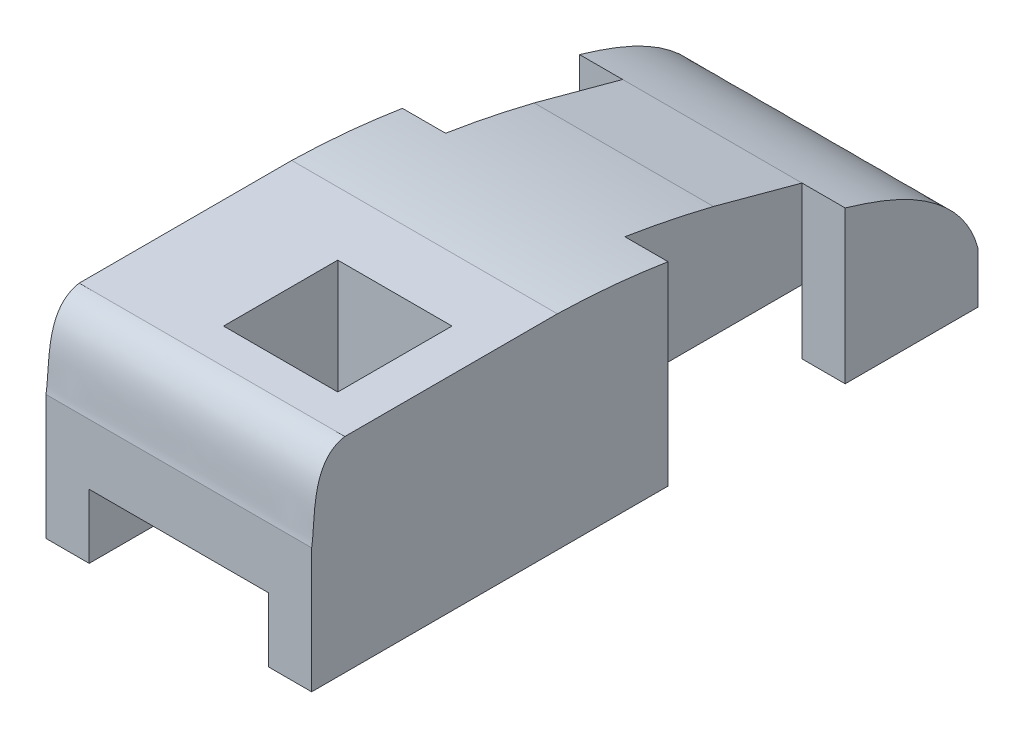
SolidWorks part; units mm, degrees
ref_plane "前视基准面" through (0, 0, 0) normal (0, 0, 1) x (1, 0, 0)
ref_plane "上视基准面" through (0, 0, 0) normal (0, 1, 0) x (1, 0, 0)
ref_plane "右视基准面" through (0, 0, 0) normal (1, 0, 0) x (0, 0, -1)
other "Configuration Table"
sketch "草图1" plane through (0, 0, 0) normal (0, 1, 0) x (1, 0, 0)
  line L1 (-50, 92.5) -> (50, 92.5)
  line L2 (-50, 92.5) -> (-50, -92.5)
  line L3 (-50, -92.5) -> (50, -92.5)
  line L4 (50, 92.5) -> (50, -92.5)
  line L5 (-50, 92.5) -> (50, -92.5) construction
  line L6 (-50, -92.5) -> (50, 92.5) construction
  point P0 (0, 0)
  dimension "D1" = 100
  dimension "D2" = 185
extrude "凸台-拉伸1" add sketch "草图1" along normal blind 100
sketch "草图2" plane through (0, 0, 92.5) normal (0, 0, 1) x (1, 0, 0)
  line L0 (-20.8417, 0) -> (-20.8417, 3.8) construction
  line L1 (-50, 0) -> (50, 0) construction
  line L2 (-20.8417, 3.8) -> (75.1632, 3.8) construction
  line L3 (75.1632, 3.8) -> (-71.0613, 3.8) construction
  line L4 (-50, 5.664) -> (-50, -9.7456) construction
  line L5 (-50, 100) -> (-50, 0) construction
  line L7 (50, 0) -> (-50, 0)
  line L8 (50, 0) -> (50, 3.8)
  line L9 (50, 3.8) -> (-50, 3.8)
  line L10 (-50, 0) -> (-50, 3.8)
  dimension "D1" = 3.8
extrude "切除-拉伸1" cut sketch "草图2" against normal offset from surface (155 mm away) 30 up to face at (0, 50, -92.5)
sketch "草图3" plane through (0, 0, 92.5) normal (0, 0, 1) x (1, 0, 0)
  line L0 (-20, 101.4471) -> (-20, -5.8655) construction
  line L1 (-4.3, 4.1859) -> (4.3, 4.1859) construction
  line L2 (-50, 3.8) -> (-20, 3.8) construction
  line L3 (-50, 3.8) -> (50, 3.8) construction
  line L4 (50, 3.8) -> (20, 3.8) construction
  line L5 (50, 3.8) -> (-50, 3.8) construction
  line L6 (20, 3.8) -> (20, 102.7774) construction
  line L7 (0, 0) -> (0, 12.6714) construction
  line L8 (-3.51, 3.8) -> (3.51, 3.8)
  line L9 (0, 3.8) -> (7.456, 3.8) construction
  line L10 (-9.3719, 10.6927) -> (9.3719, 10.6927) construction
  line L11 (-4.5, 11.5021) -> (4.5, 11.5021) construction
  line L12 (-9.3719, 10.6927) -> (-9.3719, 3.8) construction
  line L13 (-9.3719, 10.6927) -> (-4.3, 4.1859)
  line L14 (-4.3, 4.1859) -> (-4.3, 3.8) construction
  line L15 (8.9765, 11.5021) -> (8.9765, 10.6927) construction
  line L16 (9.3719, 10.6927) -> (4.3, 4.1859)
  line L17 (-4.5, 11.5021) -> (-8.9765, 11.5021)
  line L18 (4.5, 11.5021) -> (8.9765, 11.5021)
  line L19 (-8.9765, 11.5021) -> (-8.9765, 10.6927) construction
  line L21 (-4.5, 16.0021) -> (4.5, 16.0021) construction
  line L24 (-50, 100) -> (-50, 3.8) construction
  line L25 (-50, 16.0021) -> (-50, 3.8)
  line L26 (-50, 3.8) -> (-3.51, 3.8)
  line L28 (50, 100) -> (50, 3.8) construction
  line L29 (50, 16.0021) -> (50, 3.8)
  line L30 (50, 3.8) -> (3.51, 3.8)
  line L33 (20.5, 3.8) -> (3.51, 3.8)
  line L36 (-20.5, 3.8) -> (-3.51, 3.8)
  line L37 (0, 16.0021) -> (4, 16.0021)
  line L38 (0, 16.0021) -> (-4, 16.0021)
  line L39 (4, 16.0021) -> (4, 12.0021)
  line L40 (-4, 16.0021) -> (-4, 12.0021)
  line L41 (-4, 16.0021) -> (-20, 16.0021)
  line L42 (-20, 16.0021) -> (-20, 3.8)
  line L43 (-20, 3.8) -> (-3.51, 3.8)
  line L44 (4, 16.0021) -> (20, 16.0021)
  line L45 (20, 16.0021) -> (20, 3.8)
  line L46 (20, 3.8) -> (3.51, 3.8)
  arc A0 (-4.3, 4.1859) -> (-3.51, 3.8) centre (-3.51, 4.8016) ccw
  arc A1 (3.51, 3.8) -> (4.3, 4.1859) centre (3.51, 4.8016) ccw
  arc A2 (-9.3719, 10.6927) -> (-8.9765, 11.5021) centre (-8.3456, 10.6927) cw
  arc A3 (8.9765, 11.5021) -> (9.3719, 10.6927) centre (8.9765, 11.0008) cw
  arc A4 (-4, 12.0021) -> (-4.5, 11.5021) centre (-4.5, 12.0021) cw
  arc A5 (4, 12.0021) -> (4.5, 11.5021) centre (4.5, 12.0021) ccw
  point P21 (0, 3.8)
  point P24 (0, 10.6927)
  point P28 (0, 11.5021)
  point P29 (0, 4.1859)
  line M35 (-50, 3.8) -> (50, 3.8)
  dimension "D10" = 4.5
  dimension "D1" = 30
  dimension "D2" = 30
  dimension "D3" = 7.02
  dimension "D4" = 6.8927
  dimension "D5" = 8.25
  dimension "D6" = 8.6
  dimension "D7" = 4.4765
  dimension "D8" = 9
  dimension "D9" = 4.4765
  dimension "D11" = 4
  dimension "D12" = 4
  dimension "D13" = 4
extrude "切除-拉伸2" cut sketch "草图3" against normal offset from surface (155 mm away) 30 contours A4 L40 L41 L42 L36 A0 L13 A2 L17 | L39 A5 L18 A3 L16 A1 L45 L44 M35 up to face at (0, 50, -92.5)
sketch "草图4" plane through (0, 100, 0) normal (0, 1, 0) x (1, 0, 0)
  line L0 (50, -77.1603) -> (20.5, -77.1603) construction
  line L1 (50, -92.5) -> (50, 92.5) construction
  line L2 (20.5, -77.1603) -> (20.5, -102.6857) construction
  line L3 (20.5, -102.6857) -> (20.5, 96.3461) construction
  line L4 (57.5619, -92.5) -> (57.5619, -63) construction
  line L5 (-50, -92.5) -> (50, -92.5) construction
  line L6 (-68.401, -63) -> (56.5569, -63) construction
  line L8 (20.5, -63) -> (-5, -63)
  line L9 (20.5, -63) -> (20.5, -37.5)
  line L10 (20.5, -37.5) -> (-5, -37.5)
  line L11 (-5, -63) -> (-5, -37.5)
  dimension "D1" = 29.5
  dimension "D2" = 29.5
  dimension "D3" = 25.5
  dimension "D4" = 25.5
extrude "切除-拉伸3" cut sketch "草图4" against normal blind 79
sketch "草图6" plane through (0, 100, 0) normal (0, 1, 0) x (1, 0, 0)
  line L0 (-39.7063, 92.5) -> (-39.7063, 82.5)
  line L1 (50, 92.5) -> (-50, 92.5) construction
  line L2 (-39.7063, 82.5) -> (82.0818, 82.5)
  line L3 (-39.7063, 82.5) -> (-63.7302, 82.5)
  line M6 (50, -92.5) -> (50, 92.5)
  line M7 (50, 92.5) -> (-50, 92.5)
  line M8 (-50, 92.5) -> (-50, -92.5)
  dimension "D1" = 10
extrude "切除-拉伸4" cut sketch "草图6" against normal through all contours L0 L2 M6 M7 | L3 L0 M7 M8
sketch "草图7" plane through (-50, 0, 0) normal (-1, 0, 0) x (0, 0, 1)
  line L0 (-62.5, 3.8) -> (-82.5, 3.8)
  line L1 (-82.5, 0) -> (-82.5, 100) construction
  line M3 (-82.5, 100) -> (-82.5, 0)
  line M4 (-82.5, 0) -> (-62.5, 0)
  line M5 (-62.5, 0) -> (-62.5, 3.8)
extrude "切除-拉伸5" cut sketch "草图7" against normal through all and the other way through all contours L0 M5 M3 M4
sketch "草图9" plane through (0, 0, 92.5) normal (0, 0, 1) x (1, 0, 0)
  line L0 (-9.3719, 10.6927) -> (-9.3719, 13.2927)
  line L1 (-9.3719, 13.2927) -> (-4, 13.2927)
  line L2 (-4, 12.0021) -> (-4, 16.0021) construction
  line L3 (-9.3719, 10.6927) -> (9.3719, 10.6927)
  line L4 (9.3719, 10.6927) -> (9.3719, 13.2927)
  line L5 (9.3719, 13.2927) -> (4, 13.2927)
  line L6 (4, 16.0021) -> (4, 12.0021) construction
  line L7 (-4, 13.2927) -> (4, 13.2927)
  dimension "D1" = 2.6
extrude "凸台-拉伸4" add sketch "草图9" against normal blind 160
sketch "草图10" plane through (0, 0, 92.5) normal (0, 0, 1) x (1, 0, 0)
  line L0 (-20, 16.0021) -> (-20, 17.8021)
  line L1 (-20, 17.8021) -> (-4, 17.8021)
  line L2 (-4, 17.8021) -> (-4, 16.0021)
  line L4 (4, 16.0021) -> (4, 17.8021)
  line L5 (4, 17.8021) -> (19.9985, 17.8021)
  line L6 (19.9985, 17.8021) -> (20, 16.0021)
  line L7 (20, 16.0021) -> (4, 16.0021) construction
  line L8 (4, 16.0021) -> (20, 16.0021) construction
  line L9 (-20, 16.0021) -> (-4, 16.0021)
  line L10 (4, 16.0021) -> (20, 16.0021)
  dimension "D1" = 1.8
  dimension "D2" = 1.8
extrude "切除-拉伸6" cut sketch "草图10" against normal blind 155
sketch "草图13" plane through (0, 3.8, 0) normal (0, -1, 0) x (1, 0, 0)
  line L11 (-30, 92.5) -> (-30, -82.5)
  line L12 (50, -82.5) -> (-50, -82.5) construction
  line L13 (-30, -82.5) -> (-50, -82.5)
  line L14 (-50, 92.5) -> (-30, 92.5)
  line L16 (-50, 92.5) -> (-50, -82.5)
  line L17 (50, 92.5) -> (30, 92.5)
  line L18 (50, 92.5) -> (20, 92.5) construction
  line L19 (30, 92.5) -> (30, -82.5)
  line L20 (30, -82.5) -> (50, -82.5)
  line L21 (50, -82.5) -> (50, 92.5)
  dimension "D3" = 20
  dimension "D4" = 20
extrude "切除-拉伸7" cut sketch "草图13" against normal through all
sketch "草图14" plane through (30, 0, 0) normal (1, 0, 0) x (0, 0, -1)
  line L0 (-92.5, 100) -> (-92.5, 50)
  line L1 (-92.5, 100) -> (-92.5, 3.8) construction
  line L2 (-92.5, 50) -> (82.5, 50)
  line L3 (82.5, 100) -> (82.5, 3.8) construction
  line L4 (82.5, 50) -> (82.5, 100)
  line L5 (82.5, 100) -> (-92.5, 100)
  dimension "D1" = 50
extrude "切除-拉伸8" cut sketch "草图14" against normal through all
sketch "草图15" plane through (0, 3.8, 0) normal (0, -1, 0) x (1, 0, 0)
  line L0 (-30, -82.5) -> (-30, -72.5)
  line L1 (-30, -82.5) -> (-30, 92.5) construction
  line L2 (-30, -72.5) -> (30, -72.5)
  line L3 (30, 92.5) -> (30, -82.5) construction
  line L4 (30, -72.5) -> (30, -82.5)
  line L5 (30, -82.5) -> (-30, -82.5)
  dimension "D1" = 10
extrude "切除-拉伸9" cut sketch "草图15" against normal through all
sketch "草图16" plane through (0, 50, 0) normal (0, 1, 0) x (1, 0, 0)
  line L0 (30, -92.5) -> (30, 72.5) construction
  line L1 (-30, -92.5) -> (30, -92.5)
  line L2 (-30, -92.5) -> (-30, -78)
  line L3 (-30, -78) -> (30, -78)
  line L4 (30, -92.5) -> (30, -78)
  dimension "D1" = 14.5
extrude "切除-拉伸10" cut sketch "草图16" against normal through all
sketch "草图17" plane through (30, 0, 0) normal (1, 0, 0) x (0, 0, -1)
  line L0 (-78, 3.8) -> (72.5, 3.8) construction
  line L1 (-78, 50) -> (-63, 50) construction
  line L2 (-78, 50) -> (-78, 3.8) construction
  line L3 (-78, 3.8) -> (-63, 3.8) construction
  line L4 (-63, 50) -> (-63, 3.8) construction
  line L5 (72.5, 50) -> (72.5, 3.8) construction
  line L6 (-63, 50) -> (-37.5, 50)
  line L7 (-63, 50) -> (-63, 3.8)
  line L8 (-63, 3.8) -> (-37.5, 3.8)
  line L9 (-37.5, 50) -> (-37.5, 3.8)
  line L10 (-37.5, 50) -> (-22.5, 50)
  line L11 (-37.5, 50) -> (-37.5, 3.8)
  line L12 (-37.5, 3.8) -> (-22.5, 3.8)
  line L13 (-22.5, 50) -> (-22.5, 3.8)
  line L14 (72.5, 15.3113) -> (72.5, 3.8)
  line L15 (72.5, 3.8) -> (-22.5, 3.8)
  line L16 (-22.5, 50) -> (72.5, 50)
  line L17 (72.5, 50) -> (72.5, 15.3113)
  spline S0 degree 3 poles (-22.5, 50) (-9.3307, 49.7061) (11.0858, 46.8271) (38.2398, 39.499) (59.6886, 33.2729) (70.6797, 22.2955) (72.5, 15.3113) knots 0 0 0 0 0.374533 0.581855 0.802431 1 1 1 1
  line M3 (72.5, 50) -> (-78, 50)
  line M6 (72.5, 3.8) -> (72.5, 50)
  dimension "D1" = 15
  dimension "D2" = 25.5
  dimension "D3" = 15
extrude "切除-拉伸11" cut sketch "草图17" against normal through all contours S0 M3 M6
sketch "草图24" plane through (0, 0, 78) normal (0, 0, 1) x (1, 0, 0)
  line L0 (9.3719, 11.309) -> (9.3719, 10.6927)
  line L1 (9.3719, 10.6927) -> (4.3, 4.1859) construction
  arc A0 (9.3719, 10.6927) -> (9.3719, 11.309) centre (8.9765, 11.0008) ccw construction
  arc M6 (9.3719, 10.6927) -> (9.3719, 11.309) centre (8.9765, 11.0008) ccw
extrude "切除-拉伸21" cut sketch "草图24" against normal blind 140.5 and the other way through all contours L0 M6
sketch "草图28" plane through (30, 0, 0) normal (1, 0, 0) x (0, 0, -1)
  line L0 (-78, 3.8) -> (72.5, 3.8) construction
  line L1 (-78, 50) -> (-63, 50)
  line L2 (-78, 50) -> (-78, 3.8)
  line L3 (-78, 3.8) -> (-63, 3.8)
  line L4 (-63, 50) -> (-63, 3.8)
  spline S0 degree 3 poles (-70.5, 50) (-78.4109, 48.6564) (-77.0738, 36.8433) (-78, 31.9829) knots 0 0 0 0 1 1 1 1
  line M9 (-78, 50) -> (-78, 3.8)
  dimension "D1" = 15
extrude "切除-拉伸26" cut sketch "草图28" against normal through all contours S0 L1 M9
sketch "草图34" plane through (0, 3.8, 0) normal (0, -1, 0) x (1, 0, 0)
  line L0 (-30, -72.5) -> (-30, 78) construction
  line L1 (-20, -62.5) -> (-30, -62.5)
  line L2 (-20, -62.5) -> (-20, -42.5)
  line L3 (-20, -42.5) -> (-30, -42.5)
  line L4 (-30, -62.5) -> (-30, -42.5)
  line L5 (30, 78) -> (30, -72.5) construction
  line L6 (20, -62.5) -> (30, -62.5)
  line L7 (20, -62.5) -> (20, -42.5)
  line L8 (20, -42.5) -> (30, -42.5)
  line L9 (30, -62.5) -> (30, -42.5)
  line L10 (-9.3719, -62.5) -> (-9.3719, 78) construction
  line L11 (-9.3719, -42.5) -> (9.3719, -42.5)
  line L12 (-9.3719, -42.5) -> (-9.3719, -62.5)
  line L13 (-9.3719, -62.5) -> (9.3719, -62.5)
  line L14 (9.3719, -42.5) -> (9.3719, -62.5)
  line L15 (20, -62.5) -> (3.51, -62.5) construction
  line L16 (4.3, -62.5) -> (9.3719, -62.5) construction
  line L17 (20, -62.5) -> (20, 78) construction
  line L18 (-20, -42.5) -> (-30, -42.5)
  line L19 (-20, -42.5) -> (-20, -22.5)
  line L20 (-20, -22.5) -> (-30, -22.5)
  line L21 (-30, -42.5) -> (-30, -22.5)
  line L22 (-9.3719, -22.5) -> (9.3719, -22.5)
  line L23 (-9.3719, -22.5) -> (-9.3719, -42.5)
  line L24 (-9.3719, -42.5) -> (9.3719, -42.5)
  line L25 (9.3719, -22.5) -> (9.3719, -42.5)
  line L26 (20, -22.5) -> (30, -22.5)
  line L27 (20, -22.5) -> (20, -42.5)
  line L28 (20, -42.5) -> (30, -42.5)
  line L29 (30, -22.5) -> (30, -42.5)
  line L31 (-20, -22.5) -> (-30, -22.5)
  line L32 (-20, -22.5) -> (-20, -2.5)
  line L33 (-20, -2.5) -> (-30, -2.5)
  line L34 (-30, -22.5) -> (-30, -2.5)
  line L35 (-20, -2.5) -> (-30, -2.5)
  line L36 (-20, -2.5) -> (-20, 78)
  line L37 (-20, 78) -> (-30, 78)
  line L38 (-30, -2.5) -> (-30, 78)
  line L39 (-9.3719, 78) -> (9.3719, 78)
  line L40 (-9.3719, 78) -> (-9.3719, -2.5)
  line L41 (-9.3719, -2.5) -> (9.3719, -2.5)
  line L42 (9.3719, 78) -> (9.3719, -2.5)
  line L43 (20, 78) -> (30, 78)
  line L44 (20, 78) -> (20, -2.5)
  line L45 (20, -2.5) -> (30, -2.5)
  line L46 (30, 78) -> (30, -2.5)
  line M6 (30, -72.5) -> (30, 78)
  line M8 (20, 78) -> (20, -62.5)
  line M14 (-20, -62.5) -> (-20, 78)
  line M16 (-30, 78) -> (-30, -72.5)
  dimension "D1" = 20
  dimension "D2" = 20
  dimension "D3" = 20
  dimension "D4" = 20
  dimension "D5" = 20
extrude "切除-拉伸31" cut sketch "草图34" against normal through all contours L20 L3 M14 M16 | L26 L8 M8 M6
sketch "草图35" plane through (0, 3.8, 0) normal (0, -1, 0) x (1, 0, 0)
  line L0 (-30, -22.5) -> (-30, 78) construction
  line L1 (-20, -22.5) -> (-30, -22.5)
  line L2 (-20, -22.5) -> (-20, -2.5)
  line L3 (-20, -2.5) -> (-30, -2.5)
  line L4 (-30, -22.5) -> (-30, -2.5)
  line L5 (-9.3719, -62.5) -> (-9.3719, 78) construction
  line L6 (-9.3719, -2.5) -> (9.3719, -2.5)
  line L7 (-9.3719, -2.5) -> (-9.3719, -22.5)
  line L8 (-9.3719, -22.5) -> (9.3719, -22.5)
  line L9 (9.3719, -2.5) -> (9.3719, -22.5)
  line L10 (20, -22.5) -> (20, 78) construction
  line L11 (20, -2.5) -> (30, -2.5)
  line L12 (20, -2.5) -> (20, -22.5)
  line L13 (20, -22.5) -> (30, -22.5)
  line L14 (30, -2.5) -> (30, -22.5)
  line L15 (30, 78) -> (30, -22.5) construction
  line L17 (-9.3719, 78) -> (9.3719, 78)
  line L18 (-9.3719, 78) -> (-9.3719, -2.5)
  line L19 (-9.3719, -2.5) -> (9.3719, -2.5)
  line L20 (9.3719, 78) -> (9.3719, -2.5)
  dimension "D1" = 20
extrude "切除-拉伸32" cut sketch "草图35" against normal blind 14 contours L20 L17 L18 L6
sketch "草图40" plane through (0, 0, -2.5) normal (0, 0, 1) x (1, 0, 0)
  line L0 (9.3719, 13.2927) -> (4, 13.2927) construction
  line L1 (4, 17.8021) -> (3.75, 17.8021)
  line L2 (4, 17.8021) -> (4, 13.2927)
  line L3 (4, 13.2927) -> (3.75, 13.2927)
  line L4 (3.75, 17.8021) -> (3.75, 13.2927)
  line L5 (-4, 17.8) -> (4, 17.8) construction
  line L6 (-4, 13.2927) -> (-3.75, 13.2927)
  line L7 (-4, 13.2927) -> (-4, 17.8)
  line L8 (-4, 17.8) -> (-3.75, 17.8)
  line L9 (-3.75, 13.2927) -> (-3.75, 17.8)
  line L10 (9.3719, 10.6927) -> (9.3719, 13.2927) construction
  line L11 (-9.3719, 13.2927) -> (9.3719, 13.2927)
  line L12 (-9.3719, 13.2927) -> (-9.3719, 12.7927)
  line L13 (-9.3719, 12.7927) -> (9.3719, 12.7927)
  line L14 (9.3719, 13.2927) -> (9.3719, 12.7927)
  line L16 (-3.75, 13.2927) -> (3.75, 13.2927)
  line L17 (-3.75, 13.2927) -> (-3.75, 12.7927)
  line L18 (-3.75, 12.7927) -> (3.75, 12.7927)
  line L19 (3.75, 13.2927) -> (3.75, 12.7927)
  line M7 (9.3719, 10.6927) -> (9.3719, 13.2927)
  line M8 (9.3719, 13.2927) -> (4, 13.2927)
  line M9 (4, 13.2927) -> (4, 17.8)
  line M10 (4, 17.8) -> (-4, 17.8)
  line M12 (-4, 13.2927) -> (-9.3719, 13.2927)
  line M13 (-9.3719, 13.2927) -> (-9.3719, 10.6927)
  dimension "D1" = 0.25
  dimension "D2" = 0.25
  dimension "D3" = 0.5
extrude "切除-拉伸35" cut sketch "草图40" against normal blind 60 contours L4 L3 M10 M9 | L3 L19 L13 M7 M8 | L17 L6 L13 M12 M13
sketch "草图41" plane through (0, 0, 78) normal (0, 0, 1) x (1, 0, 0)
  line L0 (-20, 3.8) -> (-30, 3.8) construction
  line L1 (-20, 17.8021) -> (19.9985, 17.8021)
  line L3 (-20, 18.3021) -> (19.9985, 18.3021)
  line L5 (-3.75, 17.8) -> (3.75, 17.8)
  line L6 (-3.75, 17.8) -> (-3.75, 18.3021)
  line L8 (3.75, 17.8) -> (3.75, 18.3021)
  line L11 (-20, 17.8) -> (-3.75, 17.8)
  line L17 (-20, 18.3021) -> (-20.25, 18.3021)
  line L18 (-20, 18.3021) -> (-20, 3.8)
  line L19 (-20, 3.8) -> (-20.25, 3.8)
  line L20 (-20.25, 18.3021) -> (-20.25, 3.8)
  line L21 (30, 3.8) -> (20, 3.8) construction
  line L22 (19.9985, 18.3021) -> (20.2485, 18.3021)
  line L23 (19.9985, 18.3021) -> (19.9985, 3.8)
  line L24 (19.9985, 3.8) -> (20.2485, 3.8)
  line L25 (20.2485, 18.3021) -> (20.2485, 3.8)
  dimension "D1" = 0.5
  dimension "D2" = 0.25
  dimension "D3" = 0.25
extrude "切除-拉伸36" cut sketch "草图41" against normal blind 140.5
sketch "草图43" plane through (0, 0, 78) normal (0, 0, 1) x (1, 0, 0)
  line L0 (-4, 17.8) -> (4, 17.8) construction
  line L1 (-4, 17.8021) -> (-3.75, 17.8021)
  line L2 (-4, 17.8021) -> (-4, 17.8)
  line L3 (-4, 17.8) -> (-3.75, 17.8)
  line L4 (-3.75, 17.8021) -> (-3.75, 17.8)
  line L5 (-4, 17.8) -> (-3.75, 17.8) construction
  line L7 (3.75, 17.8021) -> (4, 17.8021)
  line L8 (3.75, 17.8021) -> (3.75, 17.8)
  line L9 (3.75, 17.8) -> (4, 17.8)
  line L10 (4, 17.8021) -> (4, 17.8)
extrude "切除-拉伸37" cut sketch "草图43" against normal blind 140.5
sketch "草图44" plane through (0, 0, 78) normal (0, 0, 1) x (1, 0, 0)
  line L1 (-3.75, 18.3021) -> (3.75, 18.3021)
  line L2 (-3.75, 18.3021) -> (-3.75, 17.8)
  line L3 (-3.75, 17.8) -> (3.75, 17.8)
  line L4 (3.75, 18.3021) -> (3.75, 17.8)
extrude "切除-拉伸38" cut sketch "草图44" against normal offset from surface (80.4999 mm away) 0.0001 up to face at (0, 10.3288, -2.5)
sketch "草图45" plane through (0, 3.8, 0) normal (0, -1, 0) x (1, 0, 0)
  line L0 (-30, -22.5) -> (-30, 78) construction
  line L1 (-30, -2.5) -> (-20.25, -2.5)
  line L2 (-30, -2.5) -> (-30, -22.5)
  line L3 (-30, -22.5) -> (-20.25, -22.5)
  line L4 (-20.25, -2.5) -> (-20.25, -22.5)
  line L5 (-9.3719, -2.5) -> (-4.3, -2.5) construction
  line L6 (20.2485, -22.5) -> (20.2485, 78) construction
  line L7 (20.2485, -2.5) -> (30, -2.5)
  line L8 (20.2485, -2.5) -> (20.2485, -22.5)
  line L9 (20.2485, -22.5) -> (30, -22.5)
  line L10 (30, -2.5) -> (30, -22.5)
extrude "切除-拉伸39" cut sketch "草图45" against normal through all
sketch "草图46" plane through (0, 18.3021, 0) normal (0, -1, 0) x (1, 0, 0)
  line L1 (20, -22.5) -> (20.2485, -22.5)
  line L2 (20, -22.5) -> (20, -42.5)
  line L3 (20, -42.5) -> (20.2485, -42.5)
  line L4 (20.2485, -22.5) -> (20.2485, -42.5)
  line L5 (-20, -22.5) -> (-20.25, -22.5)
  line L6 (-20, -22.5) -> (-20, -42.5)
  line L7 (-20, -42.5) -> (-20.25, -42.5)
  line L8 (-20.25, -22.5) -> (-20.25, -42.5)
extrude "凸台-拉伸5" add sketch "草图46" against normal through all
sketch "草图47" plane through (-20.25, 0, 0) normal (-1, 0, 0) x (0, 0, 1)
  spline S0 degree 1 poles (-42.5, 38.204) (-22.5, 43.618) knots 0 0 1 1
  line M3 (-22.5, 43.618) -> (-22.5, 50)
  line M4 (-22.5, 50) -> (-42.5, 50)
  line M5 (-42.5, 50) -> (-42.5, 38.204)
extrude "切除-拉伸40" cut sketch "草图47" against normal through all and the other way through all contours S0 M5 M3 M4
sketch "草图54" plane through (0, 50, 0) normal (0, 1, 0) x (1, 0, 0)
  line L1 (20.5, -37.5) -> (-5, -37.5)
  line L2 (20.5, -37.5) -> (20.5, -37)
  line L3 (20.5, -37) -> (-5, -37)
  line L4 (-5, -37.5) -> (-5, -37)
  line L5 (-5, -37) -> (-5.5, -37)
  line L6 (-5, -37) -> (-5, -63)
  line L7 (-5, -63) -> (-5.5, -63)
  line L8 (-5.5, -37) -> (-5.5, -63)
  dimension "D1" = 0.5
  dimension "D2" = 0.5
extrude "切除-拉伸41" cut sketch "草图54" against normal blind 29 contours L4 L1 L2 L3 | L5 L8 L7 L6
sketch "草图55" plane through (0, 50, 0) normal (0, 1, 0) x (1, 0, 0)
  line L1 (-5.5, -37) -> (20.5, -37)
  line L2 (-5.5, -37) -> (-5.5, -63)
  line L3 (-5.5, -63) -> (20.5, -63)
  line L4 (20.5, -37) -> (20.5, -63)
extrude "凸台-拉伸6" add sketch "草图55" against normal blind 29
sketch "草图56" plane through (0, 50, 0) normal (0, 1, 0) x (1, 0, 0)
  line L0 (-30, -70.5) -> (-30, -22.5) construction
  line L1 (-5.3, -36.8) -> (20.5, -36.8)
  line L2 (-5.3, -36.8) -> (-5.3, -62.6)
  line L3 (-5.3, -62.6) -> (20.5, -62.6)
  line L4 (20.5, -36.8) -> (20.5, -62.6)
  line L7 (-5.3, -36.8) -> (-30, -36.8) construction
  line L8 (-30, -63.4) -> (-30, -36.8) construction
  line L9 (-5.3967, -62.6) -> (-5.3967, -78) construction
  line L10 (-30, -78) -> (30, -78) construction
  line L11 (30, -70.5) -> (30, -22.5) construction
  line L12 (20.5, -36.8) -> (30, -36.8) construction
  line L13 (20.5, -36.8) -> (20.5, -62.6) construction
  line L14 (20.5, -62.6) -> (30, -62.6) construction
  line L15 (30, -36.8) -> (30, -62.6) construction
  dimension "D1" = 9.5
  dimension "D2" = 15.4
  dimension "D3" = 25.8
  dimension "D4" = 25.8
extrude "切除-拉伸42" cut sketch "草图56" against normal blind 29
